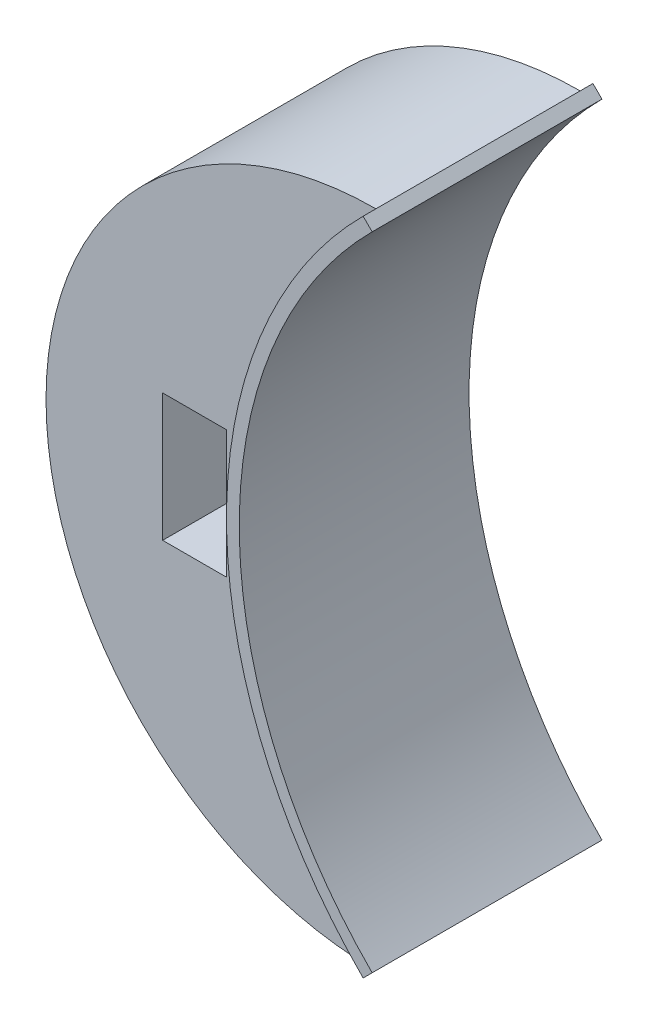
SolidWorks part; units mm, degrees
ref_plane "前视基准面" through (0, 0, 0) normal (0, 0, 1) x (1, 0, 0)
ref_plane "上视基准面" through (0, 0, 0) normal (0, 1, 0) x (1, 0, 0)
ref_plane "右视基准面" through (0, 0, 0) normal (1, 0, 0) x (0, 0, -1)
sketch "Sketch2" plane through (0, 0, 0) normal (0, 0, 1) x (1, 0, 0)
  line L0 (0, 0) -> (-25.8377, 25.8377)
  line L1 (0, 0) -> (-25.8377, -25.8377)
  arc A0 (-25.1306, 25.1306) -> (-25.1306, -25.1306) centre (0, 0) ccw
  arc A1 (-25.8377, 25.8377) -> (-25.8377, -25.8377) centre (0, 0) ccw
extrude "Boss-Extrude1" add sketch "Sketch2" along normal mid plane 18 contours L0 A1 L1 A0
sketch "Sketch3" plane through (0, 0, 0) normal (0, 0, 1) x (1, 0, 0)
  line L0 (-37.54, 0) -> (-37.54, -18.3168) construction
  line L1 (-37.54, 5) -> (-37.54, -5)
  line L2 (-28.4177, 0) -> (2.8954, 0) construction
  line L3 (-31.4845, 5) -> (-10.2392, 5) construction
  line L4 (-31.4845, -5) -> (-10.2392, -5) construction
  line L5 (-37.54, 5) -> (-37.54, 0)
  line L6 (-0.5486, 0) -> (-45.1062, 0) construction
  arc A0 (-25.8377, 25.8377) -> (-25.8377, -25.8377) centre (0, 0) ccw construction
  arc A2 (-25.8377, 25.8377) -> (-25.8377, -25.8377) centre (0, 0) ccw
  arc A4 (-25.8377, 25.8377) -> (-37.54, 5) centre (-4.2333, 0) ccw
  arc A5 (-37.54, -5) -> (-25.8377, -25.8377) centre (-4.2333, 0) ccw
  point P5 (-36.54, 0)
  point P15 (0, 0)
  dimension "D1" = 1
  dimension "D2" = 10
extrude "Boss-Extrude2" add sketch "Sketch3" along normal mid plane 16
sketch "Sketch4" plane through (0, 0, 0) normal (0, 0, 1) x (1, 0, 0)
  line L0 (-42.54, 5) -> (-42.54, -5)
  line L1 (-4.5138, 0) -> (-56.516, 0) construction
  line L2 (-37.54, 5) -> (-37.54, -5) construction
  arc A0 (-25.8377, 25.8377) -> (-42.54, 5) centre (-14.9524, 0) ccw
  arc A1 (-25.8377, 25.8377) -> (-25.8377, -25.8377) centre (-25.8377, 0) ccw
  arc A2 (-42.54, -5) -> (-25.8377, -25.8377) centre (-14.9524, 0) ccw
  dimension "D1" = 5
  dimension "D3" = 5
extrude "Boss-Extrude3" add sketch "Sketch4" along normal mid plane 16 separate body
sketch "Sketch5" plane through (0, 0, 0) normal (0, 0, 1) x (1, 0, 0)
  line L0 (-42.54, 5) -> (-37.54, 5)
  line L1 (-42.54, -5) -> (-37.54, -5)
  arc A0 (-37.54, -5) -> (-25.8377, -25.8377) centre (-4.2333, 0) ccw construction
  arc A1 (-42.54, -5) -> (-25.8377, -25.8377) centre (-14.9524, 0) ccw construction
  arc A2 (-25.8377, 25.8377) -> (-37.54, 5) centre (-4.2333, 0) ccw construction
  arc A3 (-25.8377, 25.8377) -> (-42.54, 5) centre (-14.9524, 0) ccw construction
  arc A4 (-37.54, -5) -> (-25.8377, -25.8377) centre (-4.2333, 0) ccw
  arc A5 (-42.54, -5) -> (-25.8377, -25.8377) centre (-14.9524, 0) ccw
  arc A6 (-25.8377, 25.8377) -> (-37.54, 5) centre (-4.2333, 0) ccw
  arc A7 (-25.8377, 25.8377) -> (-42.54, 5) centre (-14.9524, 0) ccw
extrude "Boss-Extrude4" add sketch "Sketch5" along normal mid plane 16
